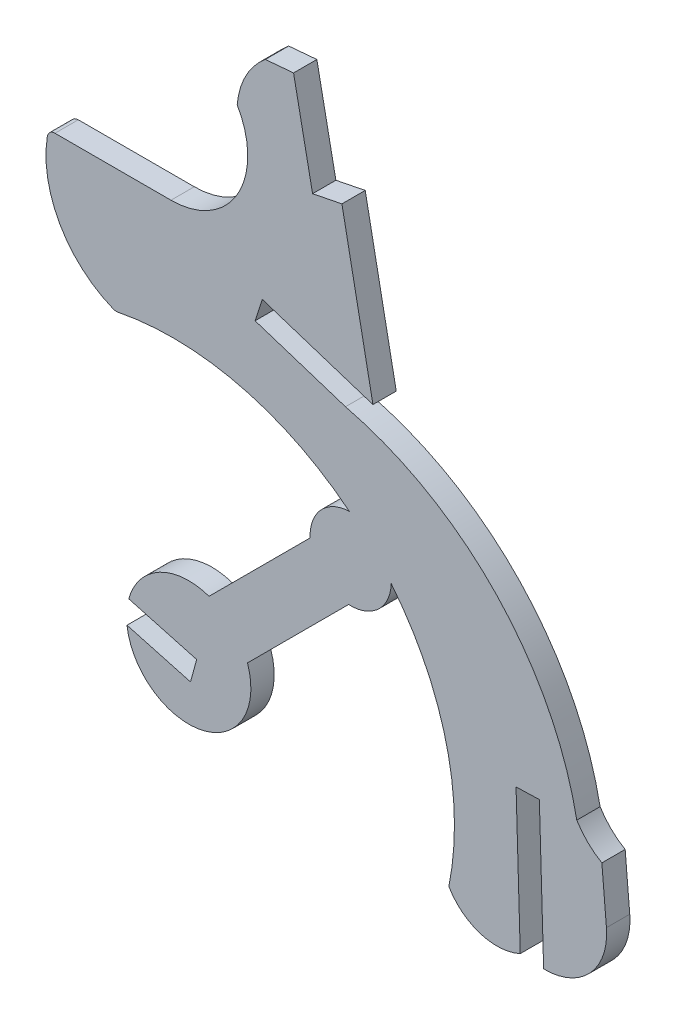
SolidWorks part; units mm, degrees
ref_plane "Front" through (0, 0, 0) normal (0, 0, 1) x (1, 0, 0)
ref_plane "Top" through (0, 0, 0) normal (0, 1, 0) x (1, 0, 0)
ref_plane "Right" through (0, 0, 0) normal (1, 0, 0) x (0, 0, -1)
sketch "Sketch1" plane through (0, 0, 0) normal (0, 0, 1) x (1, 0, 0)
  line L0 (293.9898, 734.1976) -> (308.2301, 729.5867)
  line L1 (298.0147, 761.4447) -> (294.38, 761.1265)
  line L2 (300.1524, 710.6903) -> (287.135, 697.6729)
  line L3 (305.1022, 705.7406) -> (292.0848, 692.7232)
  line L4 (304.6979, 727.5771) -> (293.0657, 731.3435)
  line L5 (276.806, 692.22) -> (285.5443, 689.8322)
  line L6 (276.5784, 689.1722) -> (284.7536, 686.9383)
  line L7 (284.7536, 686.9383) -> (285.5443, 689.8322)
  line L11 (293.0657, 731.3435) -> (293.9898, 734.1976)
  line L12 (282.2387, 739.3685) -> (267.3098, 739.3685)
  line L13 (304.2376, 749.96) -> (308.2301, 729.5867)
  line L14 (329.6475, 696.2727) -> (330.1979, 677.6751)
  line L15 (327.1908, 677.8697) -> (326.6488, 696.184)
  line L16 (326.6488, 696.184) -> (329.6475, 696.2727)
  line L17 (338.281, 686.3087) -> (337.6927, 693.2396)
  line L18 (300.4619, 749.2051) -> (298.0147, 761.4447)
  line L19 (304.2376, 749.96) -> (300.4619, 749.2051)
  arc A0 (305.1962, 716.1652) -> (275.395, 723.4732) centre (282.4746, 687.9256) ccw
  arc A1 (266.3223, 738.5264) -> (274.8281, 723.5255) centre (279.9587, 736.3465) ccw
  arc A2 (282.2387, 739.3685) -> (290.7609, 754.2544) centre (282.2387, 749.2509) ccw
  arc A3 (287.135, 697.6729) -> (276.806, 692.22) centre (284.5231, 690.1113) ccw
  arc A4 (276.5784, 689.1722) -> (292.0848, 692.7232) centre (284.5231, 690.1113) ccw
  arc A6 (294.38, 761.1265) -> (290.7609, 754.2544) centre (300.6893, 753.4147) ccw
  arc A7 (318.0035, 680.7528) -> (327.1908, 677.8697) centre (324.1854, 684.3725) ccw
  arc A8 (334.4658, 696.3874) -> (304.6979, 727.5771) centre (295.2077, 688.7192) ccw
  arc A9 (318.0035, 680.7528) -> (310.578, 710.8156) centre (282.4746, 687.9256) ccw
  arc A10 (305.1022, 705.7406) -> (310.578, 710.8156) centre (305.3628, 710.951) ccw
  arc A11 (305.1962, 716.1652) -> (300.1524, 710.6903) centre (305.3628, 710.951) ccw
  arc A12 (330.1979, 677.6751) -> (338.281, 686.3087) centre (330.3477, 685.6354) ccw
  arc A13 (334.4658, 696.3874) -> (337.6927, 693.2396) centre (342.3072, 701.198) ccw
  arc A14 (266.3223, 738.5264) -> (267.3098, 739.3685) centre (267.3098, 738.3685) cw
  arc A15 (275.395, 723.4732) -> (274.8281, 723.5255) centre (275.1996, 724.4539) cw
  dimension "D1" = 1
extrude "Base-Extrude" add sketch "Sketch1" along normal blind 3
